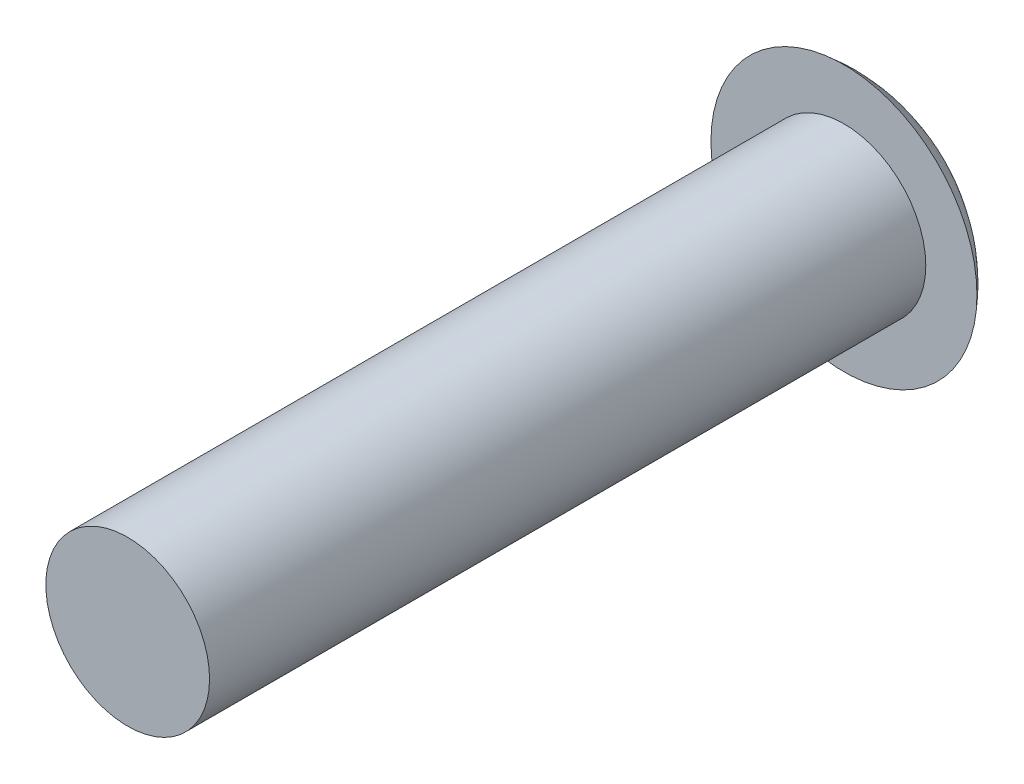
SolidWorks part; units mm, degrees
ref_plane "Front Plane" through (0, 0, 0) normal (0, 0, 1) x (1, 0, 0)
ref_plane "Top Plane" through (0, 0, 0) normal (0, 1, 0) x (1, 0, 0)
ref_plane "Right Plane" through (0, 0, 0) normal (1, 0, 0) x (0, 0, -1)
sketch "Sketch1" plane through (0, 0, 0) normal (0, 1, 0) x (1, 0, 0)
  line L0 (0, 0) -> (0, 41.7894) construction
  line L1 (0, 0) -> (-1.6, 0)
  line L2 (-1.6, 0) -> (-1.6, 14)
  line L3 (-1.6, 14) -> (-2.6, 14)
  line L4 (0, 15) -> (-0.5, 15)
  line L5 (0, 0) -> (0, 15)
  arc A0 (-2.6, 14) -> (-0.5, 15) centre (-0.5, 12.295) cw
  dimension "D1" = 1.6
  dimension "D2" = 14
  dimension "D3" = 1
  dimension "D4" = 0.5
  dimension "D5" = 1
revolve "Revolve1" add sketch "Sketch1" angle 360 about L0
